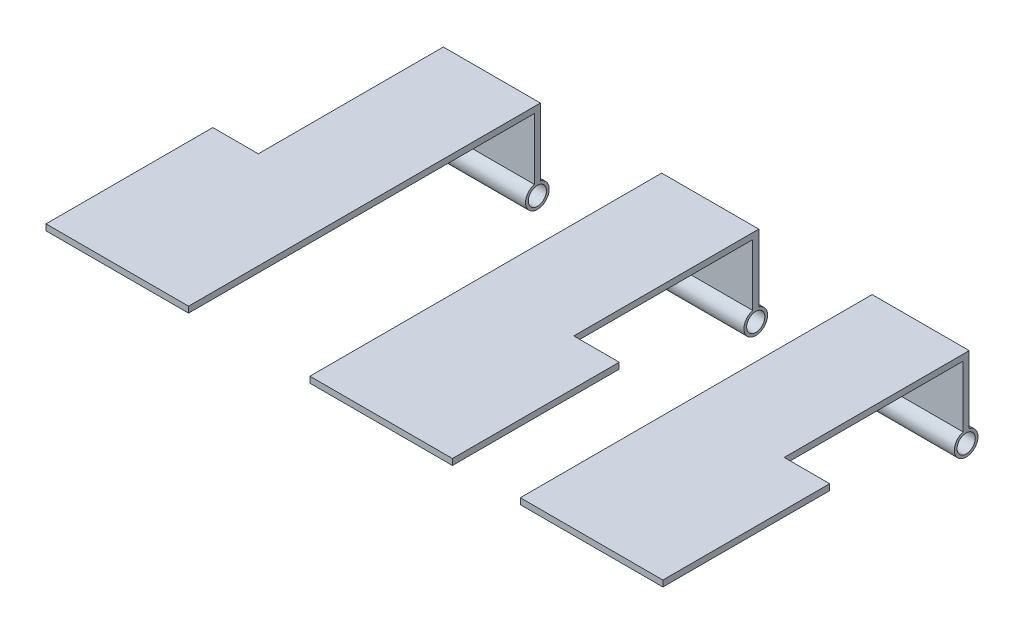
SolidWorks part; units mm, degrees
ref_plane "Front Plane" through (0, 0, 0) normal (0, 0, 1) x (1, 0, 0)
ref_plane "Top Plane" through (0, 0, 0) normal (0, 1, 0) x (1, 0, 0)
ref_plane "Right Plane" through (0, 0, 0) normal (1, 0, 0) x (0, 0, -1)
sketch "Sketch1" plane through (0, 0, 0) normal (1, 0, 0) x (0, 0, -1)
  line L0 (0, 0) -> (0, 1.95)
  line L1 (0, 13) -> (0.4995, 13)
  line L2 (0.4995, 13) -> (-0.5005, 13)
  line L3 (-0.5005, 13) -> (-0.5005, 1.8847)
  line L4 (0.4995, 13) -> (0.4995, 1.8849)
  arc A0 (-0.5005, 1.8847) -> (0.4995, 1.8849) centre (0, 0) ccw
  circle A1 centre (0, 0) radius 1.5
extrude "Boss-Extrude1" add sketch "Sketch1" along normal blind 16
sketch "Sketch2" plane through (0, 13, 0) normal (0, 1, 0) x (1, 0, 0)
  line L0 (0, 0) -> (0, -57.5)
  line L1 (0, 0) -> (16, -0.0005)
  line L2 (16, -0.5005) -> (16, 0.4995) construction
  line L3 (16, -0.0005) -> (16, -30.0005)
  line L4 (0, -57.5) -> (23.5, -57.5)
  line L5 (16, -30.0005) -> (23.5, -30.0005)
  line L6 (23.5, -30.0005) -> (23.5, -57.5)
extrude "Boss-Extrude2" add sketch "Sketch2" against normal blind 1
ref_plane "Plane1" through (16, 13, -0.4995) normal (0, 0, -1) x (-1, 0, 0)
move or copy body "Body-Move/Copy2" bodies to move or copy 102 copy yes number of copies 1 translate (-34.6909, 0, 0)
ref_plane "Plane3" through (-44.6909, 0, 0) normal (-1, 0, 0) x (0, 0, 1)
mirror "Mirror4" about plane through (-44.6909, 0, 0) normal (-1, 0, 0) of bodies 104
split "Split1" trim tools "Plane3" bodies to split 105 102 resulting bodies 106 107
